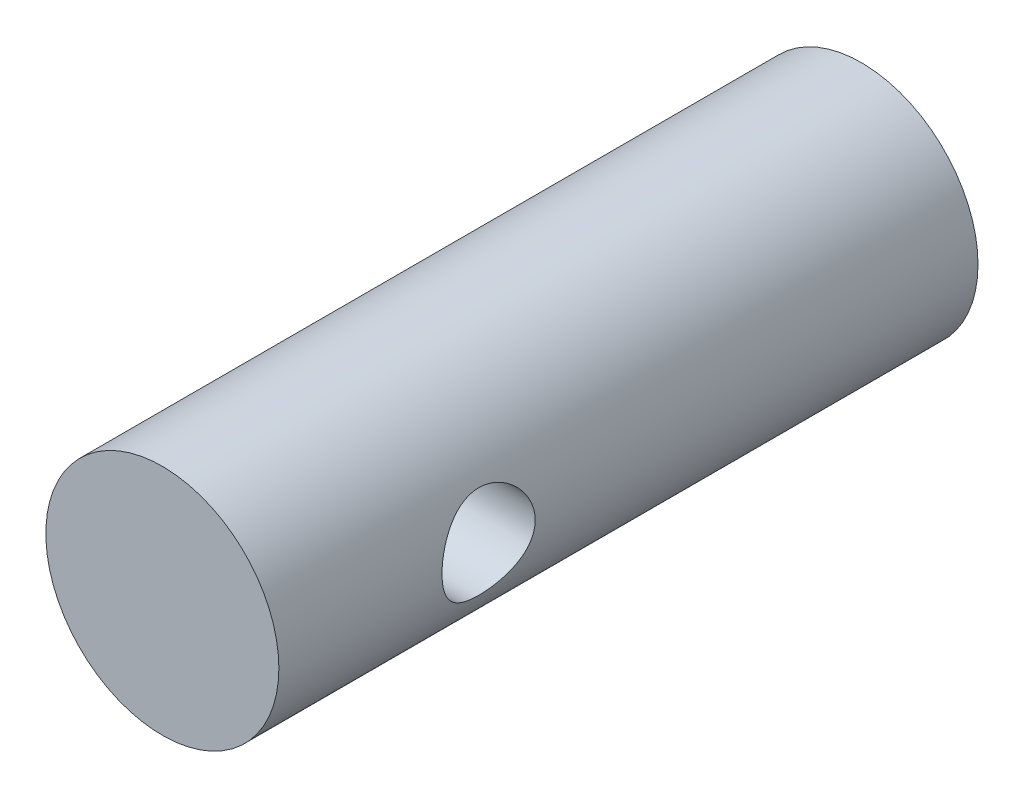
SolidWorks part; units mm, degrees
material "AISI 304"
ref_plane "Front Plane" through (0, 0, 0) normal (0, 0, 1) x (1, 0, 0)
ref_plane "Top Plane" through (0, 0, 0) normal (0, 1, 0) x (1, 0, 0)
ref_plane "Right Plane" through (0, 0, 0) normal (1, 0, 0) x (0, 0, -1)
sketch "Sketch1" plane through (0, 0, 0) normal (0, 0, 1) x (1, 0, 0)
  circle A0 centre (0, 0) radius 5
  dimension "D1" = 10
extrude "Boss-Extrude1" add sketch "Sketch1" against normal blind 30
ref_plane "Plane1" through (-5, 0, 0) normal (-1, 0, 0) x (0, 0, 1)
sketch "Sketch2" plane through (-5, 0, 0) normal (-1, 0, 0) x (0, 0, 1)
  circle A0 centre (-9, 0) radius 2
  point P0 (-9, 0)
  dimension "D1" = 4
extrude "Cut-Extrude1" cut sketch "Sketch2" against normal up to next contours A0
cosmetic thread "Cosmetic Thread1" parameters "D2"=5
